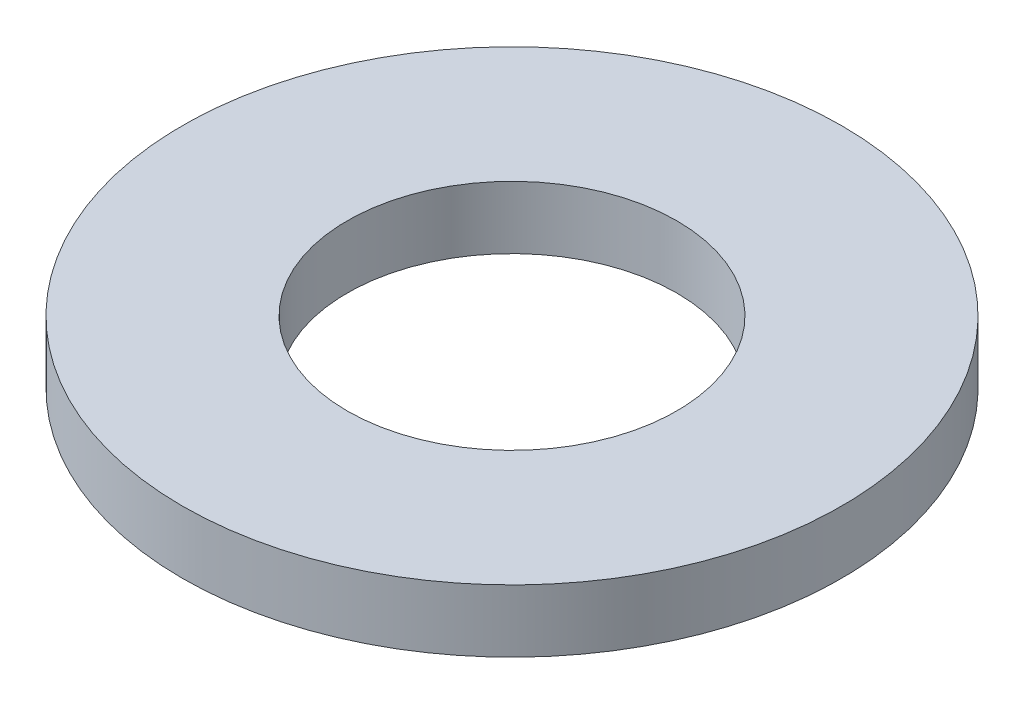
SolidWorks part; units mm, degrees
ref_plane "Front Plane" through (0, 0, 0) normal (0, 0, 1) x (1, 0, 0)
ref_plane "Top Plane" through (0, 0, 0) normal (0, 1, 0) x (1, 0, 0)
ref_plane "Right Plane" through (0, 0, 0) normal (1, 0, 0) x (0, 0, -1)
sketch "Sketch1" plane through (0, 0, 0) normal (0, 1, 0) x (1, 0, 0)
  circle A0 centre (0, 0) radius 3
  circle A1 centre (0, 0) radius 6
  dimension "D1" = 6
  dimension "D2" = 12
extrude "Boss-Extrude1" add sketch "Sketch1" along normal blind 1.14
